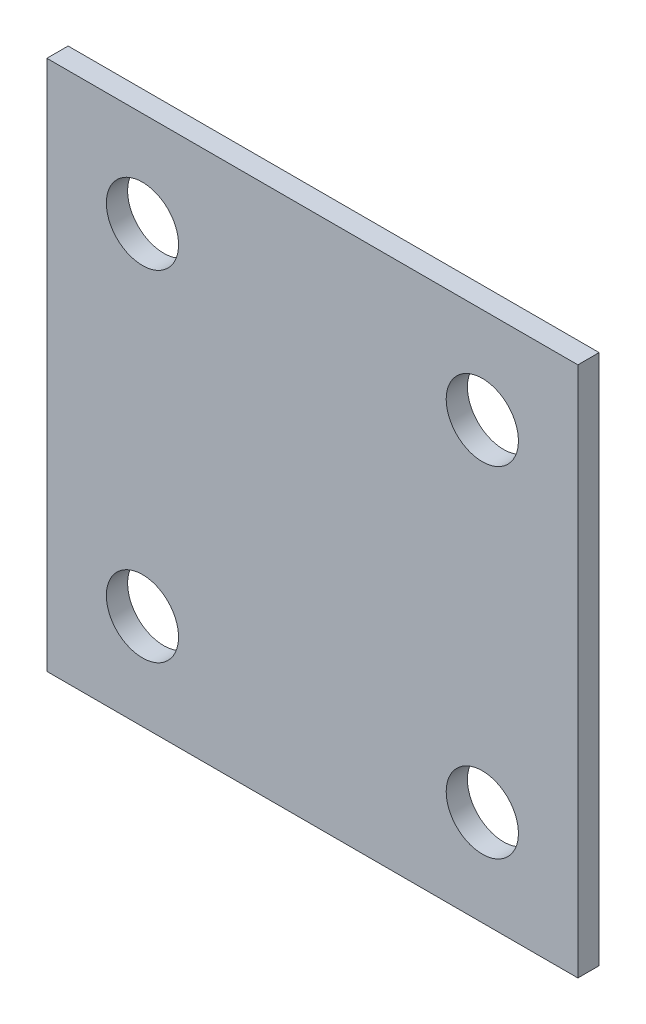
SolidWorks part; units mm, degrees
ref_plane "Plan de face" through (0, 0, 0) normal (0, 0, 1) x (1, 0, 0)
ref_plane "Plan de dessus" through (0, 0, 0) normal (0, 1, 0) x (1, 0, 0)
ref_plane "Plan de droite" through (0, 0, 0) normal (1, 0, 0) x (0, 0, -1)
sketch "Esquisse1" plane through (0, 0, 0) normal (0, 0, 1) x (1, 0, 0)
  line L1 (12.5, -12.5) -> (-12.5, -12.5)
  line L2 (12.5, -12.5) -> (12.5, 12.5)
  line L3 (12.5, 12.5) -> (-12.5, 12.5)
  line L4 (-12.5, -12.5) -> (-12.5, 12.5)
  line L5 (12.5, -12.5) -> (-12.5, 12.5) construction
  line L6 (12.5, 12.5) -> (-12.5, -12.5) construction
  point P0 (0, 0)
  dimension "D1" = 25
extrude "Boss.-Extru.1" add sketch "Esquisse1" along normal blind 1
hole_wizard "Dégagement M31" positions "Esquisse2" profile "Esquisse3" hole size "M3" standard "DIN" end condition through all
sketch "Esquisse2" plane through (0, 0, 0) normal (0, 0, -1) x (-1, 0, 0)
  point P0 (8, -8)
  point P2 (8, 8)
  point P4 (-8, 8)
  point P6 (-8, -8)
  dimension "D1" = 16
  dimension "D2" = 16
  dimension "D3" = 8
  dimension "D4" = 8
sketch "Esquisse3" plane through (-8, -8, 0) normal (1, 0, 0) x (0, 1, 0)
  line L0 (0, 0) -> (0, 1)
  line L1 (0, 1) -> (1.7, 1)
  line L2 (1.7, 1) -> (1.7, 0)
  line L5 (1.7, 0) -> (0, 0)
  line L11 (0, -6.35) -> (0, 107.95) construction
  dimension "Diamètre du perçage jusqu'au prochain" = 3.4
  dimension "Profondeur du perçage jusqu'au prochain" = 1
equation "\"d\"= 16"
equation "\"D1@Esquisse2\"=\"d\""
equation "\"D2@Esquisse2\"=\"d\""
equation "\"D3@Esquisse2\"=\"d\"/2"
equation "\"D4@Esquisse2\"=\"d\"/2"
